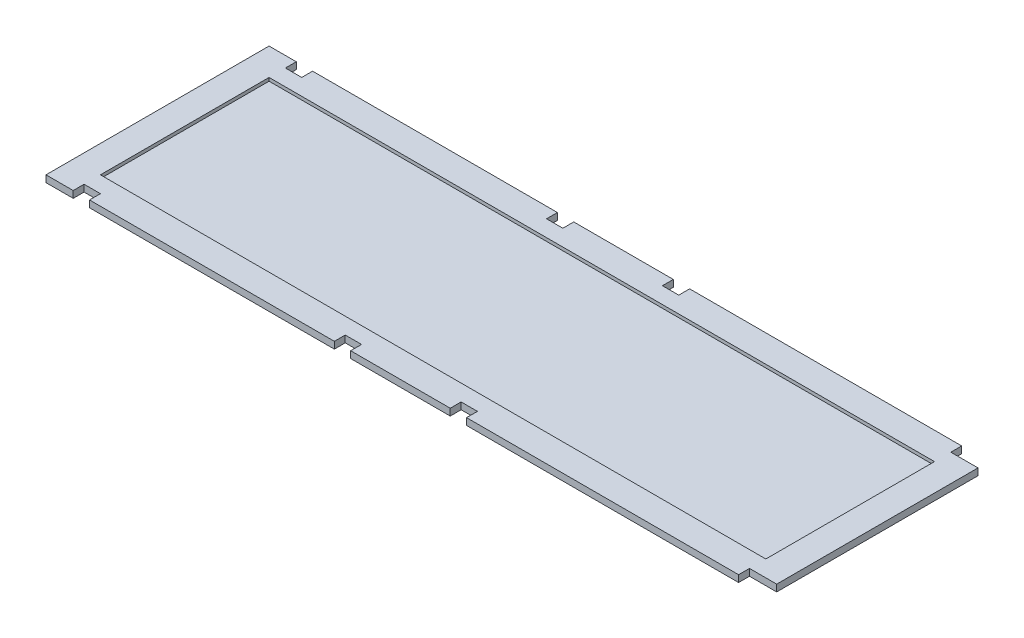
SolidWorks part; units mm, degrees
ref_plane "Front Plane" through (0, 0, 0) normal (0, 0, 1) x (1, 0, 0)
ref_plane "Top Plane" through (0, 0, 0) normal (0, 1, 0) x (1, 0, 0)
ref_plane "Right Plane" through (0, 0, 0) normal (1, 0, 0) x (0, 0, -1)
sketch "Sketch1" plane through (0, 0, 0) normal (0, 1, 0) x (1, 0, 0)
  line L0 (8, 0) -> (53, 0)
  line L1 (0, 0) -> (5, 0)
  line L2 (0, 0) -> (0, 41)
  line L3 (0, 41) -> (5, 41)
  line L4 (132.3, 2) -> (132.3, 39)
  line L6 (127.3, 41) -> (127.3, 39)
  line L7 (127.3, 39) -> (132.3, 39)
  line L10 (127.3, 0) -> (127.3, 2)
  line L11 (127.3, 2) -> (132.3, 2)
  line L14 (5, 41) -> (5, 39)
  line L15 (5, 39) -> (8, 39)
  line L16 (8, 41) -> (8, 39)
  line L18 (5, 0) -> (5, 2)
  line L19 (5, 2) -> (8, 2)
  line L20 (8, 0) -> (8, 2)
  line L21 (8, 41) -> (53, 41)
  line L22 (56, 41) -> (74.3, 41)
  line L24 (53, 41) -> (53, 39)
  line L25 (53, 39) -> (56, 39)
  line L26 (56, 41) -> (56, 39)
  line L28 (53, 0) -> (53, 2)
  line L29 (53, 2) -> (56, 2)
  line L30 (56, 0) -> (56, 2)
  line L31 (56, 0) -> (74.3, 0)
  line L32 (77.3, 41) -> (127.3, 41)
  line L34 (74.3, 41) -> (74.3, 39)
  line L35 (74.3, 39) -> (77.3, 39)
  line L36 (77.3, 41) -> (77.3, 39)
  line L38 (74.3, 0) -> (74.3, 2)
  line L39 (74.3, 2) -> (77.3, 2)
  line L40 (77.3, 0) -> (77.3, 2)
  line L41 (77.3, 0) -> (127.3, 0)
  dimension "D1" = 132.3
  dimension "D2" = 41
  dimension "D3" = 2
  dimension "D4" = 5
  dimension "D5" = 5
  dimension "D6" = 2
  dimension "D7" = 2
  dimension "D8" = 3
  dimension "D9" = 2
  dimension "D10" = 3
  dimension "D11" = 5
  dimension "D12" = 5
  dimension "D13" = 2
  dimension "D14" = 3
  dimension "D15" = 45
  dimension "D16" = 3
  dimension "D17" = 2
  dimension "D18" = 45
  dimension "D19" = 3
  dimension "D20" = 2
  dimension "D21" = 50
  dimension "D22" = 3
  dimension "D23" = 2
  dimension "D24" = 50
extrude "Boss-Extrude1" add sketch "Sketch1" along normal blind 1.25
sketch "Sketch2" plane through (0, 1.25, 0) normal (0, 1, 0) x (1, 0, 0)
  line L0 (0, 41) -> (0, 0) construction
  line L1 (5, 36) -> (127.3, 36)
  line L2 (5, 36) -> (5, 5)
  line L3 (5, 5) -> (127.3, 5)
  line L4 (127.3, 36) -> (127.3, 5)
  line L5 (53, 41) -> (8, 41) construction
  line L6 (8, 0) -> (53, 0) construction
  line L7 (132.3, 2) -> (132.3, 39) construction
  dimension "D1" = 5
  dimension "D2" = 5
  dimension "D3" = 5
  dimension "D4" = 5
extrude "Cut-Extrude1" cut sketch "Sketch2" against normal blind 0.6
